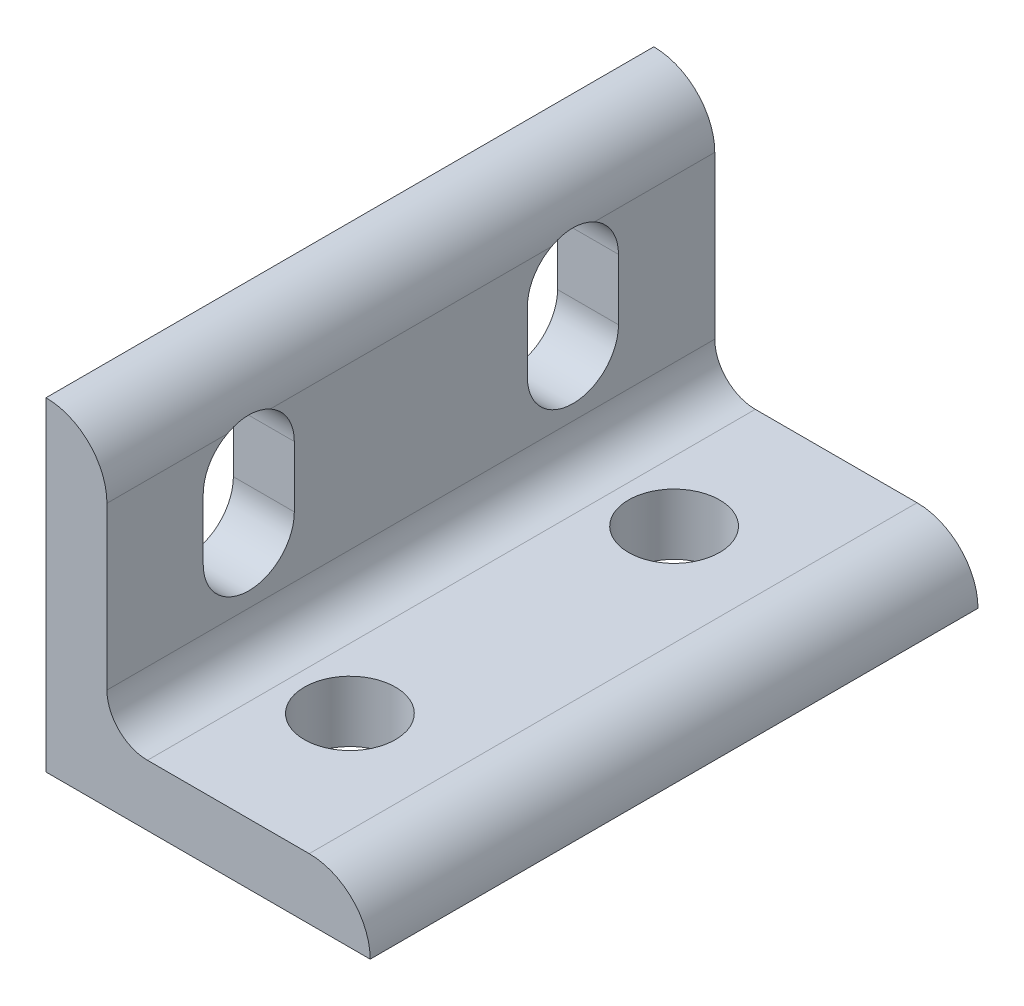
SolidWorks part; units mm, degrees
ref_plane "Front Plane" through (0, 0, 0) normal (0, 0, 1) x (1, 0, 0)
ref_plane "Top Plane" through (0, 0, 0) normal (0, 1, 0) x (1, 0, 0)
ref_plane "Right Plane" through (0, 0, 0) normal (1, 0, 0) x (0, 0, -1)
sketch "Sketch1" plane through (0, 0, 0) normal (0, 0, 1) x (1, 0, 0)
  line L0 (12.7, -12.7) -> (-12.7, -12.7) construction
  line L1 (12.7, -12.7) -> (12.7, -7.9248) construction
  line L2 (-12.7, -12.7) -> (-12.7, 12.7) construction
  point P0 (-12.7, 0)
  point P3 (0, -12.7)
  dimension "Length" = 25.4
  dimension "Thickness" = 4.7752
sketch "Sketch2" plane through (0, 0, 0) normal (1, 0, 0) x (0, 0, -1)
  line L0 (-23.8125, -12.7) -> (23.8125, -12.7) construction
  line L1 (0, -12.7) -> (0, 0) construction
  line L2 (-12.7, 4.7752) -> (-12.7, 0) construction
  line L4 (-9.1313, 4.7752) -> (-16.2687, 4.7752) construction
  point P4 (0, -12.7)
  point P12 (-12.7, 4.7752)
  dimension "Width" = 47.625
  dimension "Bottom to Slot" = 12.7
  dimension "Slot Width" = 4.7752
  dimension "Slot Dia" = 7.1374
  dimension "Slot Spacing" = 25.4
sketch "Sketch3" plane through (0, 0, 0) normal (0, 1, 0) x (1, 0, 0)
  line L0 (-3.5687, -12.7) -> (3.5687, -12.7) construction
  line L1 (12.7, 0) -> (-12.7, 0) construction
  line L2 (0, -23.8125) -> (0, 23.8125) construction
  line L3 (12.7, 0) -> (-12.7, 0) construction
  point P5 (0, -12.7)
  dimension "Hole Dia" = 7.1374
sketch "Sketch4" plane through (0, 0, 0) normal (0, 0, 1) x (1, 0, 0)
  line L0 (-12.7, 12.7) -> (-12.7, -12.7)
  line L1 (-12.7, -12.7) -> (12.7, -12.7)
  line L2 (7.9248, -7.9248) -> (-4.7498, -7.9248)
  line L3 (-7.9248, -4.7498) -> (-7.9248, 7.9248)
  arc A0 (-4.7498, -7.9248) -> (-7.9248, -4.7498) centre (-4.7498, -4.7498) cw
  arc A1 (7.9248, -7.9248) -> (12.7, -12.7) centre (7.9248, -12.7) cw
  arc A2 (-7.9248, 7.9248) -> (-12.7, 12.7) centre (-12.7, 7.9248) ccw
  dimension "D1" = 3.175
extrude "Boss-Extrude1" add sketch "Sketch4" against normal up to vertex (23.8125 mm away) and the other way up to vertex (23.8125 mm away) up to point (0, -12.7, -23.8125) other way up to point (0, -12.7, 23.8125)
sketch "Sketch5" plane through (-7.9248, 0, 0) normal (1, 0, 0) x (0, 0, -1)
  line L0 (-12.7, 4.7752) -> (-12.7, 0) construction
  line L1 (-9.1313, 4.7752) -> (-16.2687, 4.7752) construction
  line L2 (-9.1313, 4.7752) -> (-9.1313, 0)
  line L3 (-16.2687, 4.7752) -> (-16.2687, 0)
  line L4 (0, -12.7) -> (0, 0) construction
  line L5 (-23.8125, -12.7) -> (23.8125, -12.7) construction
  line L6 (12.7, 4.7752) -> (12.7, 0) construction
  line L7 (9.1313, 4.7752) -> (9.1313, 0)
  line L8 (16.2687, 4.7752) -> (16.2687, 0)
  arc A0 (-9.1313, 4.7752) -> (-16.2687, 4.7752) centre (-12.7, 4.7752) ccw
  arc A1 (-16.2687, 0) -> (-9.1313, 0) centre (-12.7, 0) ccw
  arc A2 (9.1313, 4.7752) -> (16.2687, 4.7752) centre (12.7, 4.7752) cw
  arc A3 (16.2687, 0) -> (9.1313, 0) centre (12.7, 0) cw
  point P5 (-12.7, 2.3876)
  point P19 (12.7, 2.3876)
extrude "Cut-Extrude1" cut sketch "Sketch5" against normal through all both and the other way through all
sketch "Sketch6" plane through (0, -7.9248, 0) normal (0, 1, 0) x (1, 0, 0)
  line L1 (-12.7, 0) -> (12.7, 0) construction
  circle A0 centre (0, -12.7) radius 3.5687
  circle A1 centre (0, 12.7) radius 3.5687
extrude "Cut-Extrude2" cut sketch "Sketch6" against normal through all
